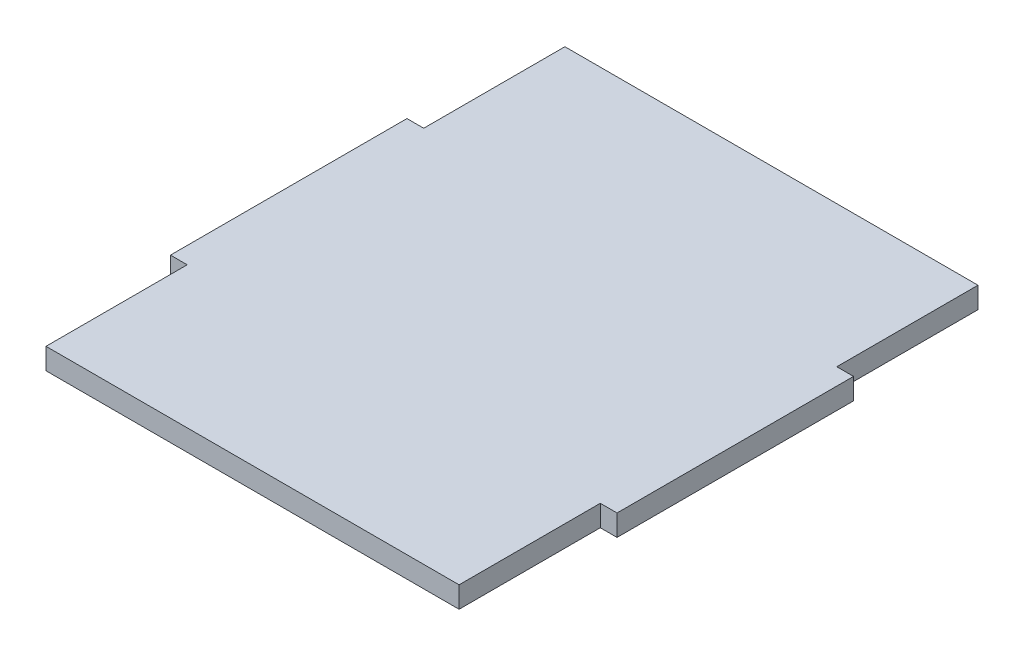
SolidWorks part; units mm, degrees
ref_plane "Alzado" through (0, 0, 0) normal (0, 0, 1) x (1, 0, 0)
ref_plane "Planta" through (0, 0, 0) normal (0, 1, 0) x (1, 0, 0)
ref_plane "Vista lateral" through (0, 0, 0) normal (1, 0, 0) x (0, 0, -1)
sketch "Croquis1" plane through (0, 0, 0) normal (0, 1, 0) x (1, 0, 0)
  line L0 (-290.4821, 184.5361) -> (-290.4821, 58.0661)
  line L1 (-290.4821, 58.0661) -> (-305.4821, 58.0661)
  line L2 (-305.4821, 58.0661) -> (-305.4821, -153.7739)
  line L3 (-305.4821, -153.7739) -> (-290.4821, -153.7739)
  line L4 (-290.4821, -153.7739) -> (-290.4821, -280.2439)
  line L5 (-290.4821, -280.2439) -> (79.5179, -280.2439)
  line L11 (79.5179, 184.5361) -> (-290.4821, 184.5361)
  line L12 (79.5179, 184.5361) -> (79.5179, 58.0661)
  line L13 (79.5179, 58.0661) -> (94.5179, 58.0661)
  line L14 (94.5179, 58.0661) -> (94.5179, -153.7739)
  line L15 (94.5179, -153.7739) -> (79.5179, -153.7739)
  line L16 (79.5179, -153.7739) -> (79.5179, -280.2439)
  dimension "D1" = 370
  dimension "D2" = 370
  dimension "D3" = 15
  dimension "D4" = 15
  dimension "D5" = 15
  dimension "D6" = 464.78
  dimension "D7" = 15
  dimension "D8" = 126.47
  dimension "D9" = 211.84
  dimension "D10" = 211.84
  dimension "D11" = 126.47
extrude "Saliente-Extruir1" add sketch "Croquis1" along normal blind 19
